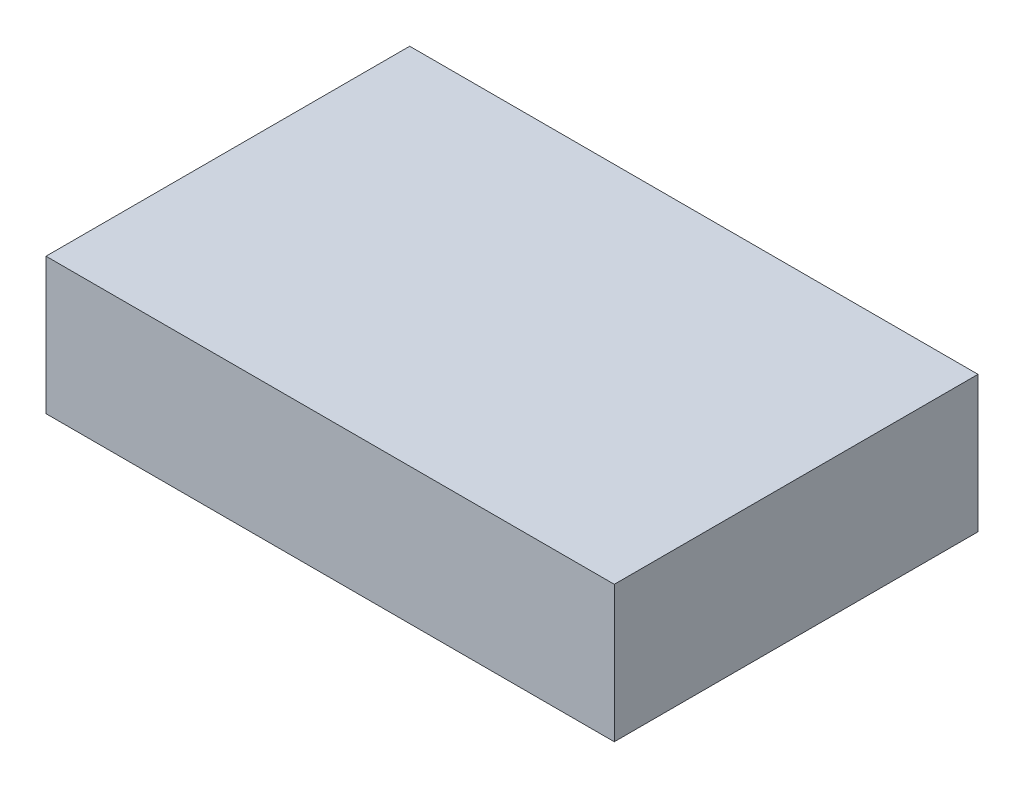
SolidWorks part; units mm, degrees
ref_plane "Front Plane" through (0, 0, 0) normal (0, 0, 1) x (1, 0, 0)
ref_plane "Top Plane" through (0, 0, 0) normal (0, 1, 0) x (1, 0, 0)
ref_plane "Right Plane" through (0, 0, 0) normal (1, 0, 0) x (0, 0, -1)
sketch "Sketch1" plane through (0, 0, 0) normal (0, 1, 0) x (1, 0, 0)
  line L1 (-125, -80) -> (125, -80)
  line L2 (-125, -80) -> (-125, 80)
  line L3 (-125, 80) -> (125, 80)
  line L4 (125, -80) -> (125, 80)
  line L5 (-125, -80) -> (125, 80) construction
  line L6 (-125, 80) -> (125, -80) construction
  point P0 (0, 0)
  dimension "D1" = 160
  dimension "D2" = 250
extrude "Boss-Extrude1" add sketch "Sketch1" along normal blind 60
